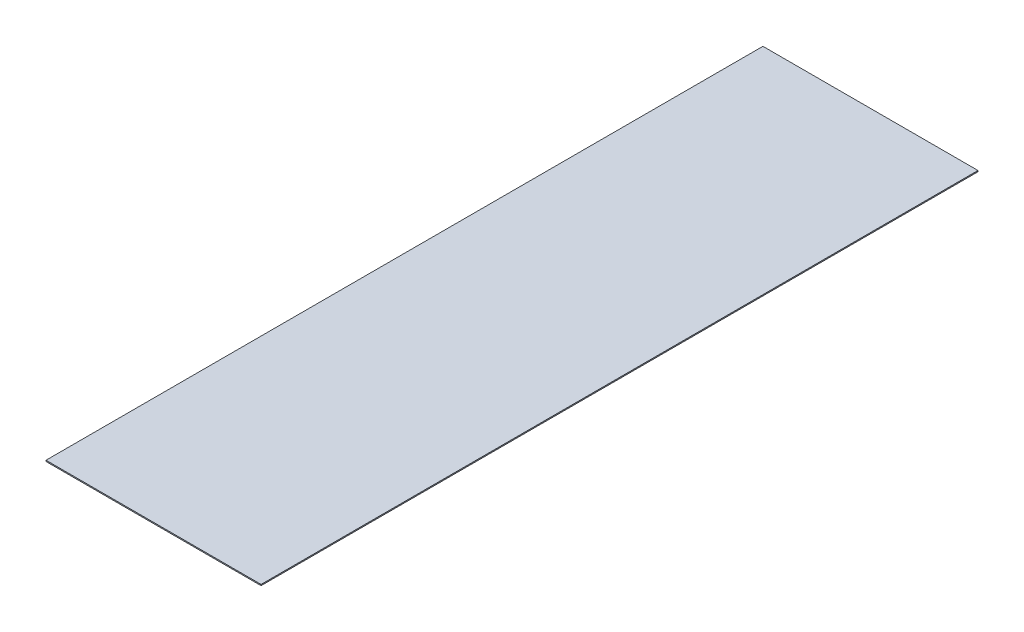
SolidWorks part; units mm, degrees
material "ASTM A36 Acero"
ref_plane "Alzado" through (0, 0, 0) normal (0, 0, 1) x (1, 0, 0)
ref_plane "Planta" through (0, 0, 0) normal (0, 1, 0) x (1, 0, 0)
ref_plane "Vista lateral" through (0, 0, 0) normal (1, 0, 0) x (0, 0, -1)
sketch "Croquis1" plane through (0, 0, 0) normal (0, 1, 0) x (1, 0, 0)
  line L1 (-457.2, -1524) -> (457.2, -1524)
  line L2 (-457.2, -1524) -> (-457.2, 1524)
  line L3 (-457.2, 1524) -> (457.2, 1524)
  line L4 (457.2, -1524) -> (457.2, 1524)
  line L5 (-457.2, -1524) -> (457.2, 1524) construction
  line L6 (-457.2, 1524) -> (457.2, -1524) construction
  point P0 (0, 0)
  dimension "D1" = 3048
  dimension "D2" = 914.4
extrude "Saliente-Extruir1" add sketch "Croquis1" along normal blind 4.8
